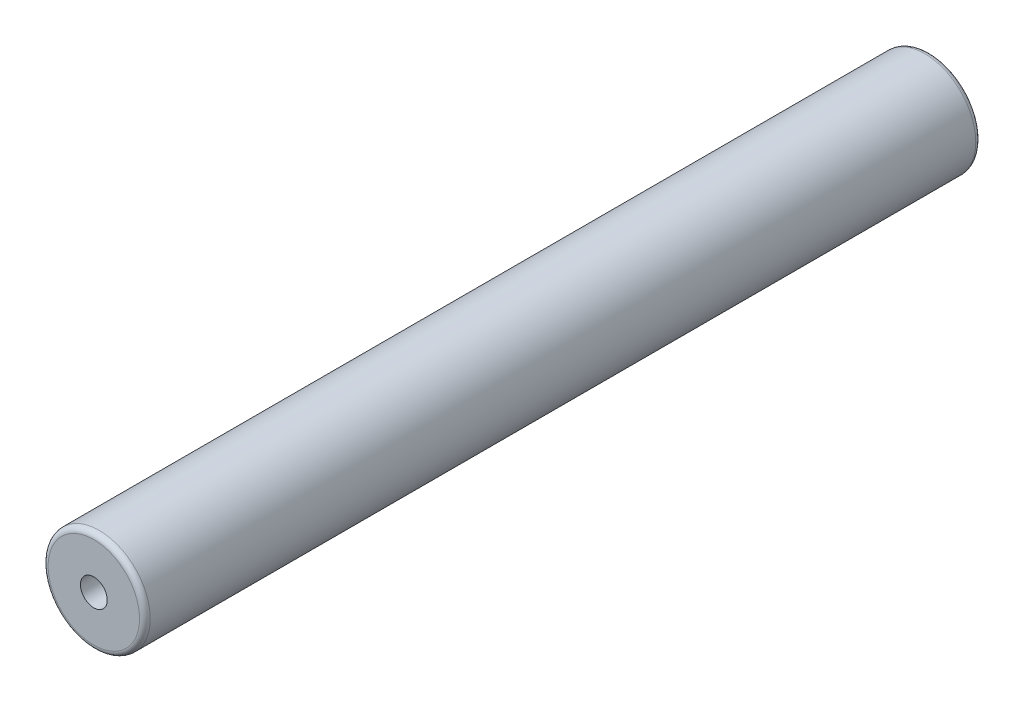
SolidWorks part; units mm, degrees
ref_plane "Plano frontal" through (0, 0, 0) normal (0, 0, 1) x (1, 0, 0)
ref_plane "Plano superior" through (0, 0, 0) normal (0, 1, 0) x (1, 0, 0)
ref_plane "Plano direito" through (0, 0, 0) normal (1, 0, 0) x (0, 0, -1)
sketch "Esboço1" plane through (0, 0, 0) normal (0, 0, 1) x (1, 0, 0)
  circle A0 centre (240.7084, 2.5961) radius 4.7625
  dimension "D1" = 9.525
extrude "Ressalto-extrusão1" add sketch "Esboço1" along normal blind 78
hole_wizard "Furo roscado de M3x0.52" positions "Esboço5" profile "Esboço4" tap size "M3x0.5" standard "Métrico Ansi"
sketch "Esboço5" plane through (0, 0, 0) normal (0, 0, -1) x (-1, 0, 0)
  point P0 (-240.7084, 2.5961)
sketch "Esboço4" plane through (240.7084, 2.5961, 0) normal (1, 0, 0) x (0, 1, 0)
  line L0 (0, 0) -> (0, 9.2511)
  line L1 (0, 9.2511) -> (1.25, 8.5)
  line L2 (1.25, 8.5) -> (1.25, 0)
  line L5 (1.25, 0) -> (0, 0)
  line L10 (0, 9.2511) -> (-1.25, 8.5) construction
  line L11 (0, -6.35) -> (0, 107.95) construction
  dimension "Tap Drill Dia." = 2.5
  dimension "Tap Drill Depth" = 8.5
  dimension "Drill Angle" = 118
cosmetic thread "Rosca de furo2" parameters "D1"=6, "D2"=3
cosmetic thread "Representação de rosca1" parameters "D1"=6, "D2"=3
fillet "Filete1" radius 0.5 1 edges at (245.4709, 2.5961, 0)
hole_wizard "Broca de rosquear para tarraxa de M3x0.51" positions "Esboço7" profile "Esboço6" hole size "M3x0.5" standard "Métrico Ansi"
sketch "Esboço7" plane through (0, 0, 78) normal (0, 0, 1) x (1, 0, 0)
  circle A0 centre (240.7084, 2.5961) radius 4.7625 construction
  point P0 (240.7084, 2.5961)
  dimension "D1" = 0
sketch "Esboço6" plane through (240.7084, 2.5961, 78) normal (1, 0, 0) x (0, -1, 0)
  line L0 (0, 0) -> (0, 5.7511)
  line L1 (0, 5.7511) -> (1.25, 5)
  line L2 (1.25, 5) -> (1.25, 0)
  line L5 (1.25, 0) -> (0, 0)
  line L10 (0, 5.7511) -> (-1.25, 5) construction
  line L11 (0, -6.35) -> (0, 107.95) construction
  dimension "Hole Dia." = 2.5
  dimension "Hole Depth" = 5
  dimension "Drill Angle" = 118
cosmetic thread "Representação de rosca2" parameters "D1"=5, "D2"=3
fillet "Filete2" radius 0.5 1 edges at (245.4709, 2.5961, 78)
